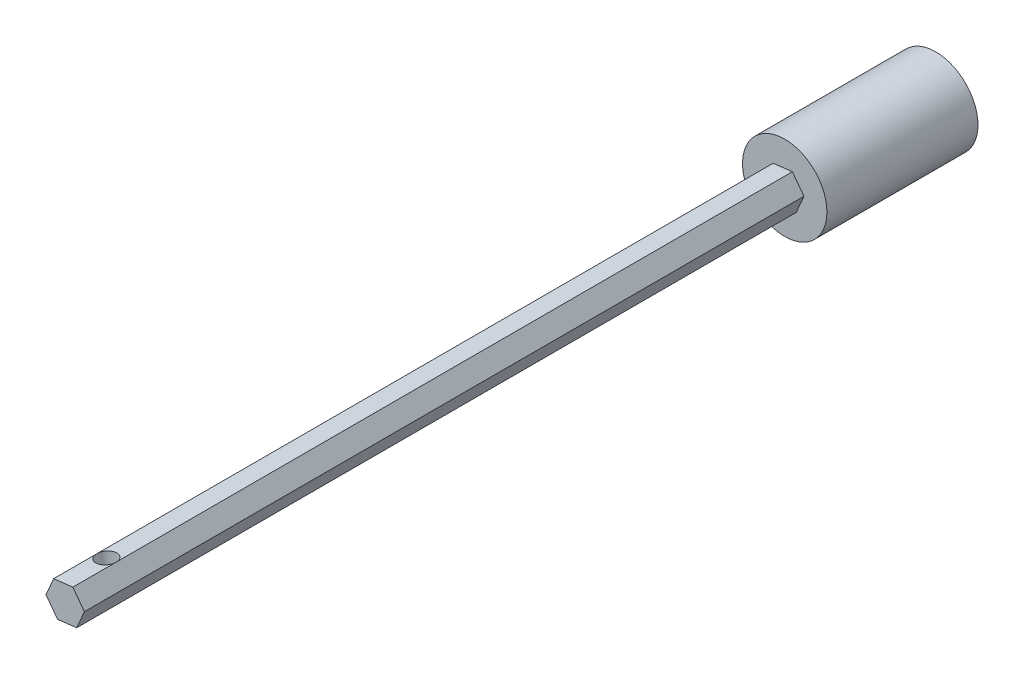
SolidWorks part; units mm, degrees
ref_plane "Front Plane" through (0, 0, 0) normal (0, 0, 1) x (1, 0, 0)
ref_plane "Top Plane" through (0, 0, 0) normal (0, 1, 0) x (1, 0, 0)
ref_plane "Right Plane" through (0, 0, 0) normal (1, 0, 0) x (0, 0, -1)
sketch "Sketch1" plane through (0, 0, 0) normal (0, 0, 1) x (1, 0, 0)
  line L1 (5.8022, 13.4694) -> (-8.7637, 11.7596)
  line L2 (-8.7637, 11.7596) -> (-14.5659, -1.7098)
  line L3 (-14.5659, -1.7098) -> (-5.8022, -13.4694)
  line L4 (-5.8022, -13.4694) -> (8.7637, -11.7596)
  line L5 (8.7637, -11.7596) -> (14.5659, 1.7098)
  line L6 (14.5659, 1.7098) -> (5.8022, 13.4694)
  circle A0 centre (0, 0) radius 12.7011 construction
extrude "Boss-Extrude1" add sketch "Sketch1" along normal blind 660.4
sketch "Sketch2" plane through (-1.4808, 12.6145, 0) normal (-0.1166, 0.9932, 0) x (0.9932, 0.1166, 0)
  line L0 (0, -660.4) -> (0, -635)
  line L1 (7.333, -660.4) -> (-7.333, -660.4) construction
  line L2 (0, -635) -> (0, -627.667)
  ellipse E0 centre (0, -627.667) end of major axis (-7.333, -627.667) minor radius 7.2764
extrude "Cut-Extrude1" cut sketch "Sketch2" against normal blind 33.02 contours E0
sketch "Sketch3" plane through (0, 0, 0) normal (0, 0, 1) x (1, 0, 0)
  circle A0 centre (0, 0) radius 32.004
  dimension "D1" = 64.008
extrude "Boss-Extrude2" add sketch "Sketch3" along normal blind 114.6048 contours A0
